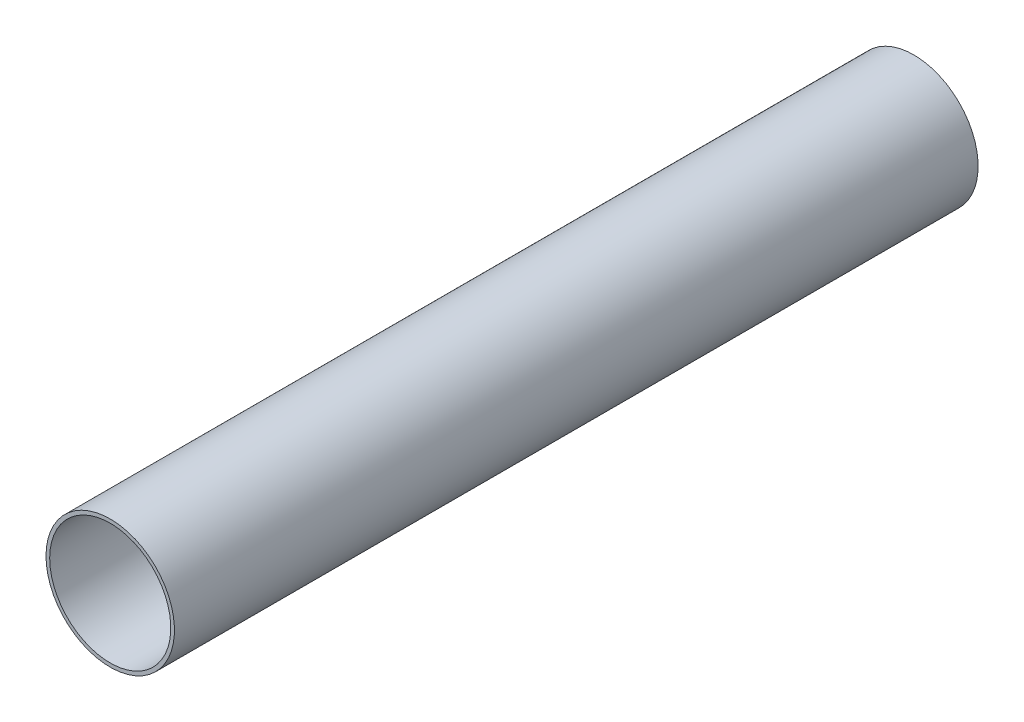
SolidWorks part; units mm, degrees
ref_plane "Front Plane" through (0, 0, 0) normal (0, 0, 1) x (1, 0, 0)
ref_plane "Top Plane" through (0, 0, 0) normal (0, 1, 0) x (1, 0, 0)
ref_plane "Right Plane" through (0, 0, 0) normal (1, 0, 0) x (0, 0, -1)
sketch "Sketch1" plane through (0, 0, 0) normal (0, 0, 1) x (1, 0, 0)
  circle A0 centre (0, 0) radius 35
  circle A1 centre (0, 0) radius 33
  dimension "D1" = 70
  dimension "D2" = 66
extrude "Boss-Extrude1" add sketch "Sketch1" along normal blind 438
